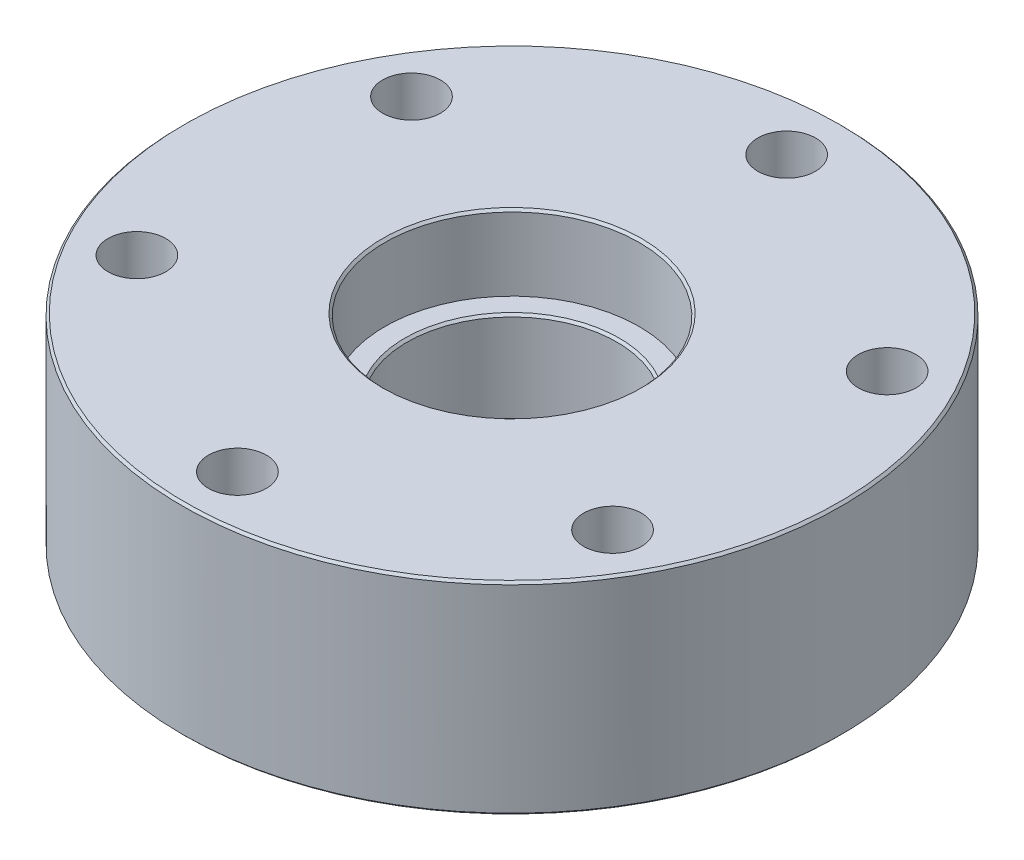
SolidWorks part; units mm, degrees
ref_plane "正面" through (0, 0, 0) normal (0, 0, 1) x (1, 0, 0)
ref_plane "平面" through (0, 0, 0) normal (0, 1, 0) x (1, 0, 0)
ref_plane "右側面" through (0, 0, 0) normal (1, 0, 0) x (0, 0, -1)
sketch "ｽｹｯﾁ2" plane through (0, 0, 0) normal (0, 0, 1) x (1, 0, 0)
  line L0 (0, 0) -> (0, 30.4518) construction
  line L1 (-9.075, 10.245) -> (-9.075, 2.245)
  line L2 (-9.075, 2.245) -> (-11, 2.245)
  line L3 (-11, 2.245) -> (-11, -0.755)
  line L4 (-11, -0.755) -> (-28.5, -0.755)
  line L5 (-28.5, -0.755) -> (-28.5, 16.745)
  line L6 (-28.5, 16.745) -> (-11, 16.745)
  line L7 (-11, 16.745) -> (-11, 10.245)
  line L8 (-11, 10.245) -> (-9.075, 10.245)
  dimension "D1" = 11
  dimension "D2" = 28.5
  dimension "D3" = 17.5
  dimension "D4" = 3
  dimension "D5" = 6.5
  dimension "D6" = 9.075
revolve "回転1" add sketch "ｽｹｯﾁ2" angle 360 about L0
sketch "ｽｹｯﾁ3" plane through (0, 16.745, 0) normal (0, 1, 0) x (1, 0, 0)
  circle A0 centre (0, 23.75) radius 2.5
  circle A1 centre (20.5681, 11.875) radius 2.5
  circle A2 centre (20.5681, -11.875) radius 2.5
  circle A3 centre (0, -23.75) radius 2.5
  circle A4 centre (-20.5681, -11.875) radius 2.5
  circle A5 centre (-20.5681, 11.875) radius 2.5
  point P16 (0, 0)
  dimension "D1" = 5
  dimension "D2" = 23.75
  dimension "D3" = 6
extrude "ｶｯﾄ - 押し出し1" cut sketch "ｽｹｯﾁ3" against normal up to surface (17.5 mm away) up to face at (0, -0.755, -11)
chamfer "面取り1" distance 0.2 angle 45 6 edges at (0, 16.745, -28.5) (0, -0.755, -28.5) (0, 10.245, -9.075) (0, 16.745, -11) (0, 2.245, -9.075) (0, -0.755, -11)
ref_plane "平面1" through (0, 7.995, 0) normal (0, 1, 0) x (1, 0, 0)
